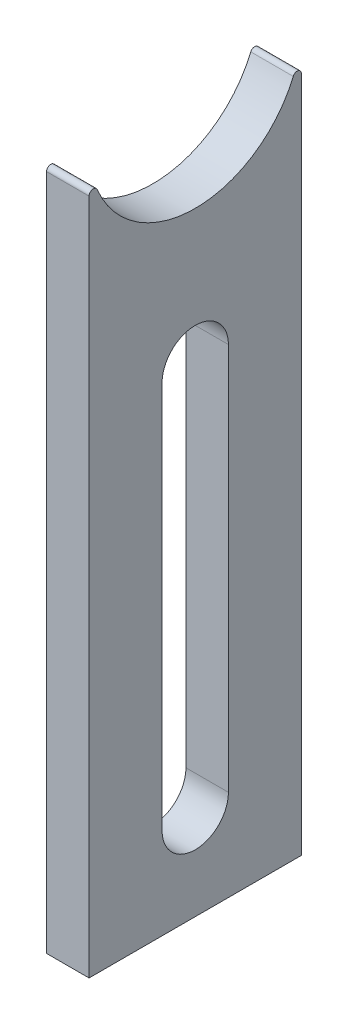
SolidWorks part; units mm, degrees
material "AISI 1020"
ref_plane "Front Plane" through (0, 0, 0) normal (0, 0, 1) x (1, 0, 0)
ref_plane "Top Plane" through (0, 0, 0) normal (0, 1, 0) x (1, 0, 0)
ref_plane "Right Plane" through (0, 0, 0) normal (1, 0, 0) x (0, 0, -1)
sketch "Sketch1" plane through (0, 0, 0) normal (1, 0, 0) x (0, 0, -1)
  line L0 (-6.35, 0) -> (6.35, 0) construction
  line L1 (-6.35, 0) -> (-6.35, -43.0366)
  line L2 (6.35, 0) -> (6.35, -43.0366)
  line L3 (-6.35, -43.0366) -> (6.35, -43.0366)
  circle A0 centre (0, 0) radius 6.35
  dimension "D1" = 12.7
extrude "Boss-Extrude1" add sketch "Sketch1" along normal blind 2.54 contours A0 L1 L3 L2
fillet "Fillet1" radius 0.254 2 edges at (1.27, 0, 6.35) (1.27, 0, -6.35)
sketch "Sketch2" plane through (0, 0, 0) normal (-1, 0, 0) x (0, 0, 1)
  line L0 (0, -6.35) -> (0, -43.0366) construction
  line L1 (6.35, -43.0366) -> (-6.35, -43.0366) construction
  line L2 (0, -14.3931) -> (0, -37.5852) construction
  line L3 (1.9844, -14.3931) -> (1.9844, -37.5852)
  line L4 (-1.9844, -14.3931) -> (-1.9844, -37.5852)
  arc A0 (-5.8615, -2.4423) -> (5.8615, -2.4423) centre (0, 0) ccw construction
  arc A1 (1.9844, -14.3931) -> (-1.9844, -14.3931) centre (0, -14.3931) ccw
  arc A2 (-1.9844, -37.5852) -> (1.9844, -37.5852) centre (0, -37.5852) ccw
  point P9 (0, -25.9891)
  dimension "D2" = 3.9688
extrude "Cut-Extrude1" cut sketch "Sketch2" against normal blind 2.54
